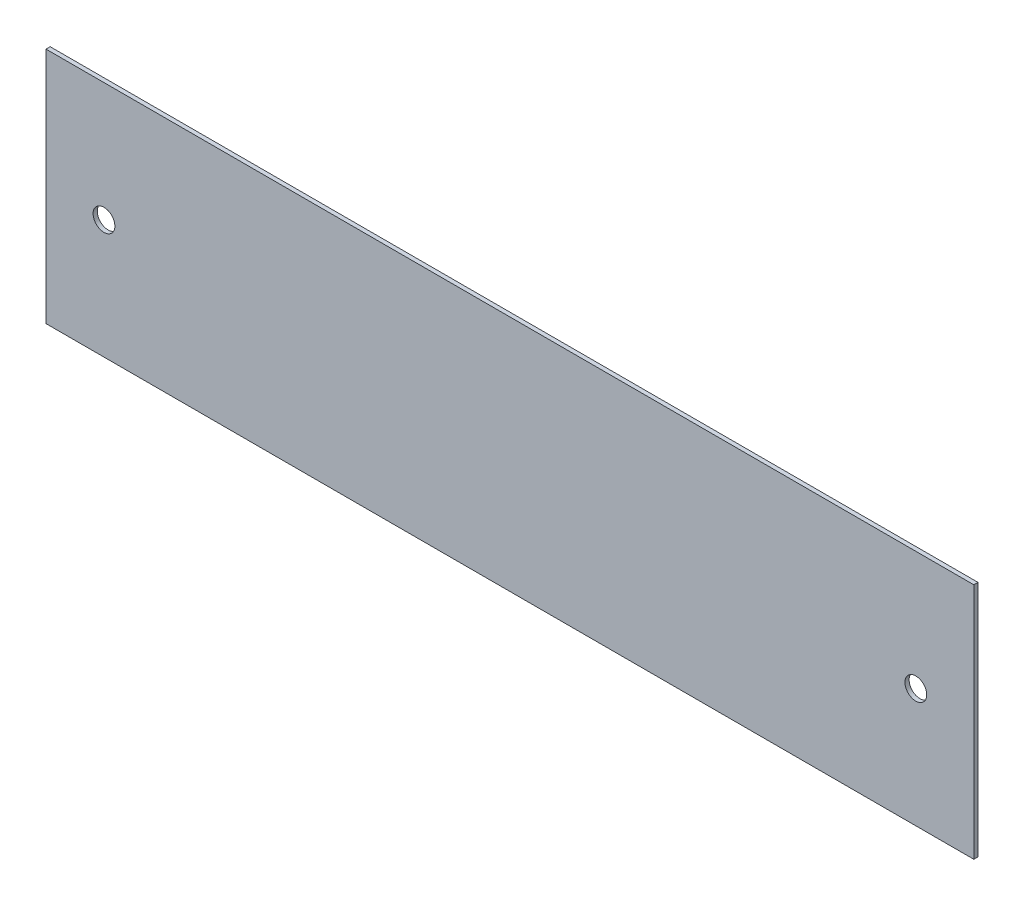
SolidWorks part; units mm, degrees
material "Alumina"
ref_plane "Front Plane" through (0, 0, 0) normal (0, 0, 1) x (1, 0, 0)
ref_plane "Top Plane" through (0, 0, 0) normal (0, 1, 0) x (1, 0, 0)
ref_plane "Right Plane" through (0, 0, 0) normal (1, 0, 0) x (0, 0, -1)
sketch "Sketch2" plane through (0, 0, 0) normal (0, 0, 1) x (1, 0, 0)
  line L1 (-144, 36.9) -> (144, 36.9)
  line L2 (-144, 36.9) -> (-144, -36.9)
  line L3 (-144, -36.9) -> (144, -36.9)
  line L4 (144, 36.9) -> (144, -36.9)
  line L5 (-144, 36.9) -> (144, -36.9) construction
  line L6 (-144, -36.9) -> (144, 36.9) construction
  point P0 (0, 0)
  dimension "D1" = 288
  dimension "D2" = 73.8
extrude "Boss-Extrude1" add sketch "Sketch2" along normal blind 1.2954
hole_wizard "1/4 Clearance Hole1" positions "Sketch3" profile "Sketch4" hole size "1/4" standard "ANSI Inch" end condition through all
sketch "Sketch3" plane through (0, 0, 1.2954) normal (0, 0, 1) x (1, 0, 0)
  line L0 (-144, 36.9) -> (-144, -36.9) construction
  line L1 (144, -36.9) -> (144, 36.9) construction
  point P0 (-126, 0)
  point P2 (126, 0)
  point P9 (0, 0)
  dimension "D1" = 18
  dimension "D2" = 18
sketch "Sketch4" plane through (-126, 0, 1.2954) normal (1, 0, 0) x (0, -1, 0)
  line L0 (0, 0) -> (0, 1.2954)
  line L1 (0, 1.2954) -> (3.3782, 1.2954)
  line L2 (3.3782, 1.2954) -> (3.3782, 0)
  line L5 (3.3782, 0) -> (0, 0)
  line L11 (0, -6.35) -> (0, 107.95) construction
  dimension "Thru Hole Dia." = 6.7564
  dimension "Thru Hole Depth" = 1.2954
